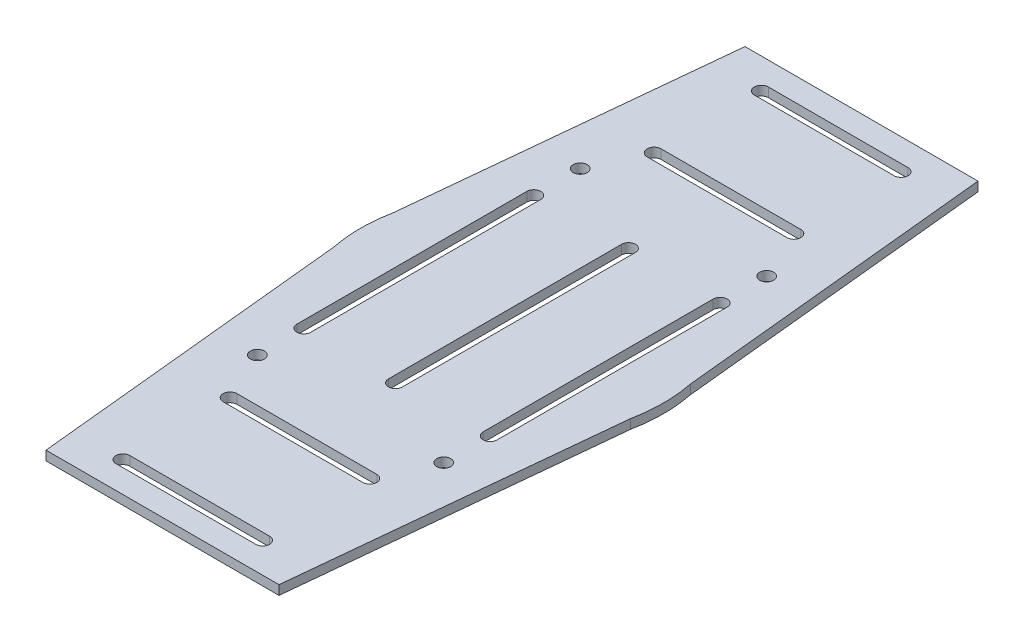
SolidWorks part; units mm, degrees
ref_plane "Front Plane" through (0, 0, 0) normal (0, 0, 1) x (1, 0, 0)
ref_plane "Top Plane" through (0, 0, 0) normal (0, 1, 0) x (1, 0, 0)
ref_plane "Right Plane" through (0, 0, 0) normal (1, 0, 0) x (0, 0, -1)
sketch "Sketch1" plane through (0, 0, 0) normal (0, 1, 0) x (1, 0, 0)
  line L0 (-31.8564, 6.4356) -> (-25, 75)
  line L1 (-25, 75) -> (25, 75)
  line L2 (0, 0) -> (0, 83.1473) construction
  line L3 (-25, -75) -> (25, -75)
  line L4 (0, 0) -> (-46.5144, 0) construction
  line L5 (-25, 75) -> (25, -75) construction
  line L6 (-25, -75) -> (25, 75) construction
  line L7 (-31.8564, -6.4356) -> (-25, -75)
  line L8 (25, 75) -> (31.8564, 6.4356)
  line L9 (31.8564, -6.4356) -> (25, -75)
  line L10 (0, 0) -> (-31.1711, 53.9899) construction
  arc A0 (-31.8564, 6.4356) -> (-31.8564, -6.4356) centre (0, 0) ccw
  arc A1 (31.8564, -6.4356) -> (31.8564, 6.4356) centre (0, 0) ccw
  circle A2 centre (-20, 34.641) radius 1.5
  circle A3 centre (20, 34.641) radius 1.5
  circle A4 centre (20, -34.641) radius 1.5
  circle A5 centre (-20, -34.641) radius 1.5
  point P0 (0, 0)
  dimension "D3" = 60
  dimension "D4" = 40
  dimension "D1" = 50
  dimension "D2" = 150
extrude "Boss-Extrude1" add sketch "Sketch1" along normal blind 2
sketch "Sketch2" plane through (0, 2, 0) normal (0, 1, 0) x (1, 0, 0)
  line L0 (-15, 68.5) -> (15, 68.5) construction
  line L1 (-15, 70) -> (15, 70)
  line L2 (-15, 67) -> (15, 67)
  line L3 (20, 24.6825) -> (20, -24.6826) construction
  line L4 (25, 75) -> (-25, 75) construction
  line L5 (0, 0) -> (0, 114) construction
  line L6 (0, 0) -> (-84.2744, 0) construction
  line L7 (-15, -68.5) -> (15, -68.5) construction
  line L8 (-15, -70) -> (15, -70)
  line L9 (-15, -67) -> (15, -67)
  line L10 (0, 57) -> (21.3407, 57) construction
  line L11 (-15, 45.5) -> (15, 45.5) construction
  line L12 (-15, 44) -> (15, 44)
  line L13 (-15, 47) -> (15, 47)
  line L14 (-15, -45.5) -> (15, -45.5) construction
  line L15 (-15, -44) -> (15, -44)
  line L16 (-15, -47) -> (15, -47)
  line L17 (-20, 24.6825) -> (-20, -24.6826) construction
  line L18 (-18.5, 24.6825) -> (-18.5, -24.6826)
  line L19 (-21.5, 24.6825) -> (-21.5, -24.6826)
  line L20 (18.5, 24.6825) -> (18.5, -24.6826)
  line L21 (21.5, 24.6825) -> (21.5, -24.6826)
  line L22 (0, 25) -> (0, -25) construction
  line L23 (1.5, 25) -> (1.5, -25)
  line L24 (-1.5, 25) -> (-1.5, -25)
  arc A0 (-15, 70) -> (-15, 67) centre (-15, 68.5) ccw
  arc A1 (15, 67) -> (15, 70) centre (15, 68.5) ccw
  circle A2 centre (-20, 34.641) radius 1.5 construction
  arc A3 (18.5, 24.6825) -> (21.5, 24.6825) centre (20, 24.6825) cw
  arc A4 (-15, -70) -> (-15, -67) centre (-15, -68.5) cw
  arc A5 (15, -67) -> (15, -70) centre (15, -68.5) cw
  arc A6 (-15, 44) -> (-15, 47) centre (-15, 45.5) cw
  arc A7 (15, 47) -> (15, 44) centre (15, 45.5) cw
  arc A8 (-15, -44) -> (-15, -47) centre (-15, -45.5) ccw
  arc A9 (15, -47) -> (15, -44) centre (15, -45.5) ccw
  arc A10 (-18.5, 24.6825) -> (-21.5, 24.6825) centre (-20, 24.6825) ccw
  arc A11 (-21.5, -24.6826) -> (-18.5, -24.6826) centre (-20, -24.6826) ccw
  arc A12 (21.5, -24.6826) -> (18.5, -24.6826) centre (20, -24.6826) cw
  arc A13 (1.5, 25) -> (-1.5, 25) centre (0, 25) ccw
  arc A14 (-1.5, -25) -> (1.5, -25) centre (0, -25) ccw
  point P2 (0, 68.5)
  point P12 (0, -68.5)
  point P13 (0, 75)
  point P26 (0, 45.5)
  point P33 (0, -45.5)
  point P40 (-20, -0.0001)
  point P48 (20, 0)
  point P55 (0, 0)
  dimension "D1" = 1.5
  dimension "D3" = 0
  dimension "D6" = 1.5
  dimension "D10" = 1.5
  dimension "D2" = 30
  dimension "D4" = 5
  dimension "D5" = 10
  dimension "D7" = 49.365
  dimension "D8" = 0.0001
  dimension "D9" = 0
  dimension "D11" = 50
extrude "Cut-Extrude1" cut sketch "Sketch2" against normal blind 2
